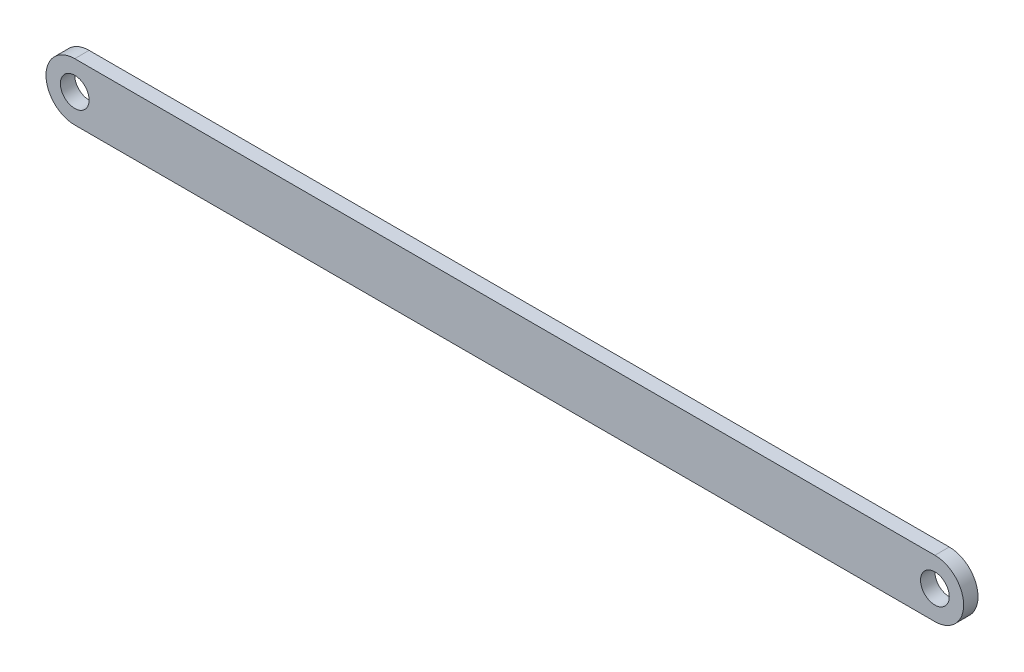
SolidWorks part; units mm, degrees
ref_plane "Plano frontal" through (0, 0, 0) normal (0, 0, 1) x (1, 0, 0)
ref_plane "Plano superior" through (0, 0, 0) normal (0, 1, 0) x (1, 0, 0)
ref_plane "Plano direito" through (0, 0, 0) normal (1, 0, 0) x (0, 0, -1)
sketch "Esboço1" plane through (0, 0, 0) normal (0, 0, 1) x (1, 0, 0)
  line L0 (-29.935, 2) -> (29.935, 2)
  line L1 (-29.935, 0) -> (29.935, 0) construction
  line L2 (-29.935, -2) -> (29.935, -2)
  arc A0 (-29.935, 2) -> (-29.935, -2) centre (-29.935, 0) ccw
  arc A1 (29.935, 2) -> (29.935, -2) centre (29.935, 0) cw
  circle A2 centre (-29.935, 0) radius 1
  circle A3 centre (29.935, 0) radius 1
  point P3 (0, 2)
  dimension "D1" = 59.87
  dimension "D2" = 2
extrude "Ressalto-extrusão1" add sketch "Esboço1" along normal blind 1
